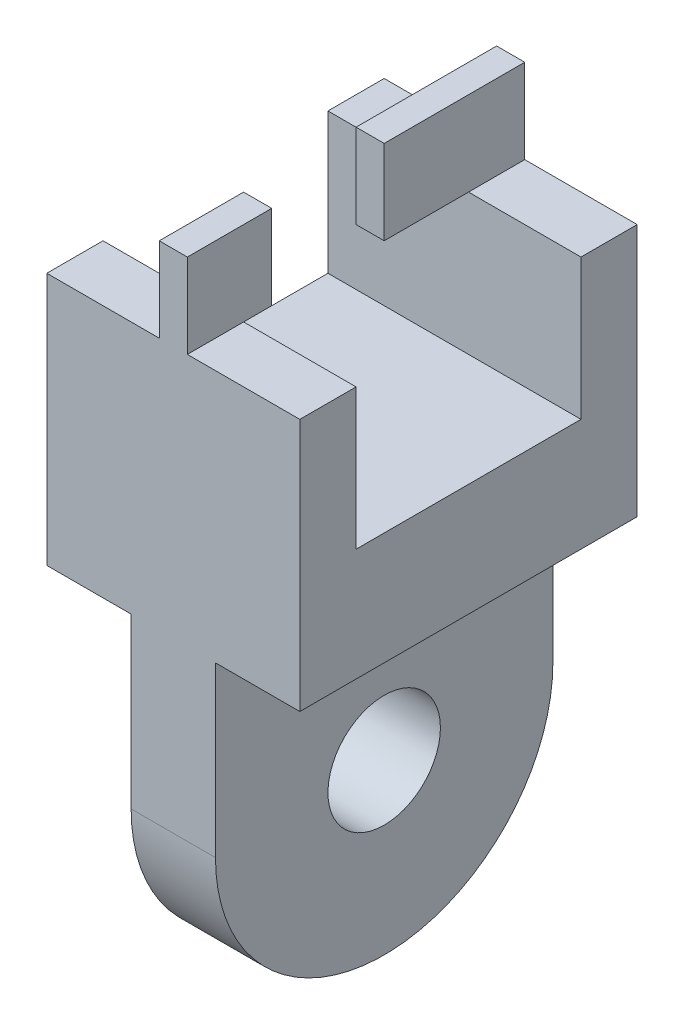
SolidWorks part; units mm, degrees
ref_plane "Front Plane" through (0, 0, 0) normal (1, 0, 0) x (0, 1, 0)
ref_plane "Top Plane" through (0, 0, 0) normal (0, 0, 1) x (0, 1, 0)
ref_plane "Right Plane" through (0, 0, 0) normal (0, 1, 0) x (-1, 0, 0)
sketch "Sketch1" plane through (0, 0, 0) normal (1, 0, 0) x (0, 1, 0)
  line L0 (0, 150) -> (450, 150)
  line L1 (450, 150) -> (450, 75)
  line L2 (450, 75) -> (375, 75)
  line L3 (375, 75) -> (375, 100)
  line L4 (375, 100) -> (250, 100)
  line L5 (250, 100) -> (250, -100)
  line L6 (250, -100) -> (375, -100)
  line L7 (375, -100) -> (375, -25)
  line L8 (375, -25) -> (450, -25)
  line L9 (450, -25) -> (450, -150)
  line L10 (450, -150) -> (0, -150)
  line L11 (150, 150) -> (150, -150)
  arc A0 (0, 150) -> (0, -150) centre (0, 0) ccw
  circle A1 centre (0, 0) radius 50
  dimension "D1" = 100
  dimension "D2" = 150
  dimension "D3" = 75
  dimension "D4" = 250
  dimension "D5" = 375
  dimension "D6" = 450
  dimension "D7" = 50
  dimension "D8" = 50
  dimension "D9" = 125
  dimension "D10" = 300
  dimension "D11" = 150
extrude "Boss-Extrude1" add sketch "Sketch1" along normal blind 112.5 contours A1 | L10 A0 L0 L1 L2 L3 L4 L5 L6 L7 L8 L9
mirror "Mirror1" about plane through (0, 0, 0) normal (1, 0, 0) of bodies 101
sketch "Sketch2" plane through (0, 0, 150) normal (0, 0, 1) x (1, 0, 0)
  line L0 (37.5, -150) -> (37.5, 150)
  line L1 (-112.5, -150) -> (112.5, -150) construction
  line L2 (37.5, 150) -> (112.5, 150)
  line L4 (12.5, 450) -> (12.5, 375)
  line L5 (112.5, 450) -> (-112.5, 450) construction
  line L6 (12.5, 375) -> (112.5, 375)
  line L9 (37.5, -150) -> (112.5, -150)
  line L10 (112.5, -150) -> (112.5, 150)
  line L11 (12.5, 450) -> (112.5, 450)
  line L12 (112.5, 450) -> (112.5, 375)
  line L13 (37.5, -150) -> (-37.5, -150)
  line L14 (-112.5, -150) -> (112.5, -150) construction
  line L15 (-37.5, -150) -> (-112.5, -150)
  line L16 (-112.5, -150) -> (-112.5, 150)
  line L18 (-112.5, 150) -> (-37.5, 150)
  line L19 (-37.5, 150) -> (-37.5, -150)
  line L20 (-12.5, 375) -> (-112.5, 375)
  line L21 (-112.5, 375) -> (-112.5, 450)
  line L22 (-112.5, 450) -> (-12.5, 450)
  line L23 (112.5, 450) -> (-112.5, 450) construction
  line L24 (-12.5, 450) -> (-12.5, 375)
  line L25 (112.5, 0) -> (-112.5, 0) construction
  line L26 (-112.5, 0) -> (-112.5, 450) construction
  point P6 (-112.5, 375)
  point P7 (-19.5882, 450)
  point P23 (112.5, 450)
  point P24 (-112.5, 450)
  point P27 (0, 0)
  point P35 (-112.5, 150)
  dimension "D1" = 100
  dimension "D2" = 125
  dimension "D3" = 300
  dimension "D4" = 150
  dimension "D5" = 75
  dimension "D6" = 375
extrude "Cut-Extrude2" cut sketch "Sketch2" against normal through all contours L10 L2 L0 L9 | L15 L16 L18 L19 | L24 L20 L21 L22 | L12 L6 L4 L11
